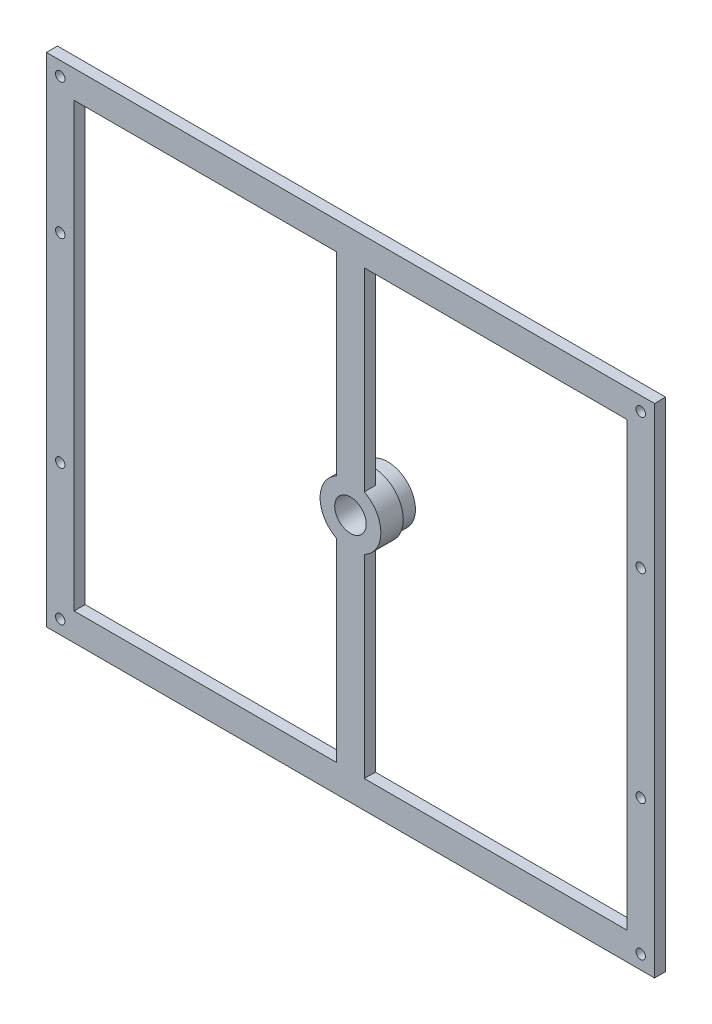
SolidWorks part; units mm, degrees
material "6061-T6 (SS)"
ref_plane "Front Plane" through (0, 0, 0) normal (0, 0, 1) x (1, 0, 0)
ref_plane "Top Plane" through (0, 0, 0) normal (0, 1, 0) x (1, 0, 0)
ref_plane "Right Plane" through (0, 0, 0) normal (1, 0, 0) x (0, 0, -1)
sketch "Sketch1" plane through (0, 0, 0) normal (0, 0, 1) x (1, 0, 0)
  line L1 (-110, -90) -> (110, -90)
  line L2 (-110, -90) -> (-110, 90)
  line L3 (-110, 90) -> (110, 90)
  line L4 (110, -90) -> (110, 90)
  line L6 (-100, -80) -> (100, -80)
  line L7 (-100, -80) -> (-100, 80)
  line L8 (-100, 80) -> (100, 80)
  line L9 (100, -80) -> (100, 80)
extrude "Upper_Perimeter" add sketch "Sketch1" along normal blind 4 from offset 304
sketch "Sketch2" plane through (0, 0, 0) normal (0, 0, 1) x (1, 0, 0)
  line L1 (-5, -85) -> (5, -85)
  line L2 (-5, -85) -> (-5, 85)
  line L3 (-5, 85) -> (5, 85)
  line L4 (5, -85) -> (5, 85)
extrude "Bearing_Spine" add sketch "Sketch2" along normal blind 4 from offset 304
sketch "Sketch3" plane through (0, 0, 0) normal (0, 0, 1) x (1, 0, 0)
  circle A0 centre (0, 0) radius 11
  circle A1 centre (0, 0) radius 5.7
extrude "Upper_Outer_Race_Stop" add sketch "Sketch3" along normal blind 8.1 from offset 299.9
sketch "Sketch4" plane through (0, 0, 0) normal (0, 0, 1) x (1, 0, 0)
  circle A0 centre (0, 0) radius 10
  circle A1 centre (0, 0) radius 6.5
extrude "Floating_Outer_Race_Seat" add sketch "Sketch4" along normal blind 5.41 from offset 294.5
sketch "Sketch5" plane through (0, 0, 308) normal (0, 0, 1) x (1, 0, 0)
  circle A0 centre (0, 0) radius 5.7
extrude "Shaft_Clip_Clearance" cut sketch "Sketch5" against normal blind 8.11
sketch "Sketch6" plane through (0, 0, 308) normal (0, 0, 1) x (1, 0, 0)
  circle A0 centre (-105, -85) radius 1.7
  circle A1 centre (-105, 85) radius 1.7
  circle A2 centre (105, -85) radius 1.7
  circle A3 centre (105, 85) radius 1.7
extrude "Four_Tie_Rod_Clearance" cut sketch "Sketch6" against normal blind 4.01
sketch "Sketch7" plane through (0, 0, 294.5) normal (0, 0, -1) x (-1, 0, 0)
  circle A0 centre (-7.188, 4.15) radius 1
  circle A1 centre (7.188, 4.15) radius 1
  circle A2 centre (0, -8.3) radius 1
extrude "Three_M2_Top_Cap_Thread_Major_Envelopes" cut sketch "Sketch7" against normal blind 4.3
sketch "Sketch8" plane through (0, 0, 308) normal (0, 0, 1) x (1, 0, 0)
  circle A0 centre (-105, -36) radius 1.7
  circle A1 centre (-105, 36) radius 1.7
  circle A2 centre (105, -36) radius 1.7
  circle A3 centre (105, 36) radius 1.7
extrude "Bench_Motor_Crossbeam_Four_D3p4" cut sketch "Sketch8" against normal blind 4.01
